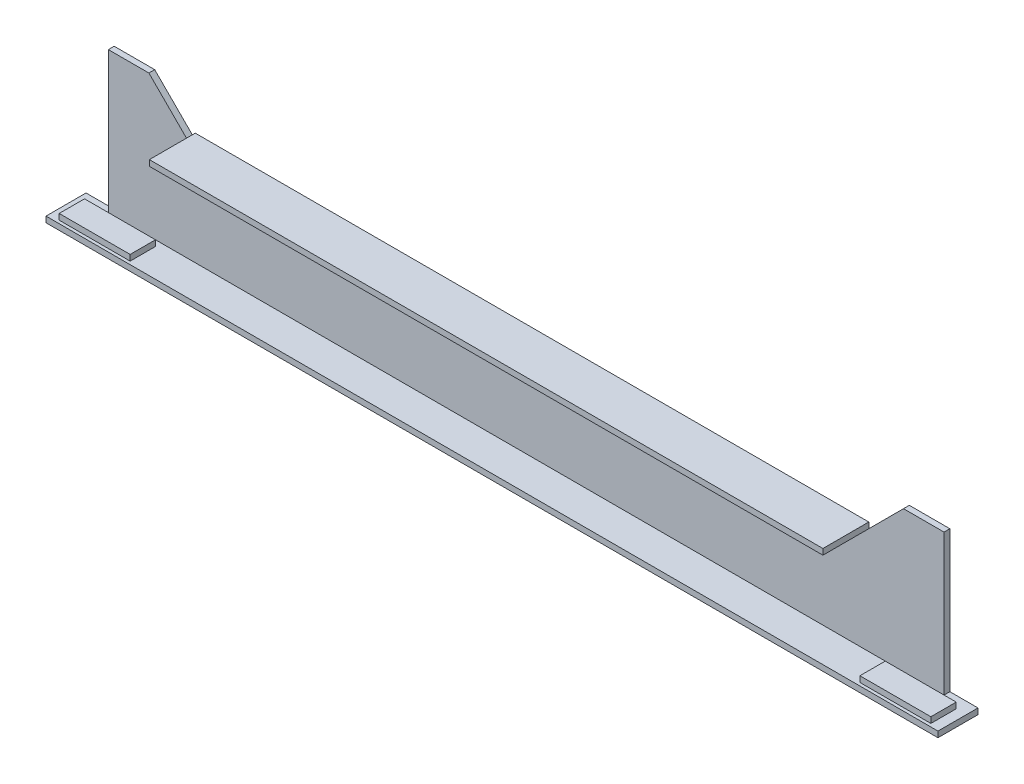
SolidWorks part; units mm, degrees
ref_plane "前视" through (0, 0, 0) normal (0, 0, 1) x (1, 0, 0)
ref_plane "上视" through (0, 0, 0) normal (0, 1, 0) x (1, 0, 0)
ref_plane "右视" through (0, 0, 0) normal (1, 0, 0) x (0, 0, -1)
sketch "草图1" plane through (0, 0, 0) normal (0, 0, 1) x (1, 0, 0)
  line L0 (0, 0) -> (1088.881, 0) construction
  line L1 (1088.881, 0) -> (-981.9373, 0) construction
  line L2 (0, 0) -> (0, 345.1364) construction
  line L3 (0, 345.1364) -> (0, -374.3029) construction
  line L4 (-744.5, 139.25) -> (-664.5, 59.25)
  line L5 (-824.5, 139.25) -> (-744.5, 139.25)
  line L6 (-824.5, 139.25) -> (-824.5, -139.25)
  line L7 (-824.5, -139.25) -> (824.5, -139.25)
  line L8 (824.5, 139.25) -> (824.5, -139.25)
  line L9 (-664.5, 59.25) -> (664.5, 59.25)
  line L10 (744.5, 139.25) -> (664.5, 59.25)
  line L11 (744.5, 139.25) -> (824.5, 139.25)
  line L12 (-784.5, 294.6321) -> (-784.5, -374.3029) construction
  point P15 (0, 59.25)
  point P17 (0, 59.25)
  dimension "D1" = 1649
  dimension "D2" = 278.5
  dimension "D3" = 80
  dimension "D4" = 80
  dimension "D5" = 80
  dimension "D6" = 40
extrude "基体-拉伸" add sketch "草图1" along normal blind 11.5
sketch "草图2" plane through (0, 0, 11.5) normal (0, 0, 1) x (1, 0, 0)
  line L0 (0, 0) -> (0, 521.0174) construction
  line L1 (-664.5, 59.25) -> (664.5, 59.25)
  line L2 (-664.5, 59.25) -> (-664.5, 70.75)
  line L3 (-664.5, 70.75) -> (664.5, 70.75)
  line L4 (664.5, 59.25) -> (664.5, 70.75)
  dimension "D1" = 11.5
extrude "凸台-拉伸7" add sketch "草图2" along normal blind 79 and the other way through all
sketch "草图3" plane through (0, 0, 11.5) normal (0, 0, 1) x (1, 0, 0)
  line L0 (0, 567.7533) -> (0, -567.7533) construction
  line L2 (880, -139.25) -> (-880, -139.25)
  line L3 (880, -139.25) -> (880, -150.75)
  line L4 (880, -150.75) -> (-880, -150.75)
  line L5 (-880, -139.25) -> (-880, -150.75)
  line L6 (-824.5, -139.25) -> (824.5, -139.25) construction
  dimension "D1" = 1760
  dimension "D2" = 11.5
extrude "凸台-拉伸9" add sketch "草图3" along normal blind 67.5 and the other way blind 11.5
sketch "草图4" plane through (0, -139.25, 0) normal (0, 1, 0) x (-1, 0, 0)
  line L0 (-937.8047, 48) -> (1011.0707, 48) construction
  line L2 (-880, 0) -> (-824.5, 0) construction
  line L4 (0, 392.3282) -> (0, -456.8038) construction
  line L5 (-720, 23) -> (-860, 23)
  line L6 (-720, 23) -> (-720, 73)
  line L7 (-720, 73) -> (-860, 73)
  line L8 (-860, 23) -> (-860, 73)
  line L10 (720, 73) -> (860, 73)
  line L11 (860, 23) -> (860, 73)
  line L12 (720, 23) -> (860, 23)
  line L13 (720, 23) -> (720, 73)
  dimension "D1" = 48
  dimension "D2" = 50
  dimension "D3" = 720
  dimension "D4" = 140
extrude "凸台-拉伸10" add sketch "草图4" along normal blind 11.5
